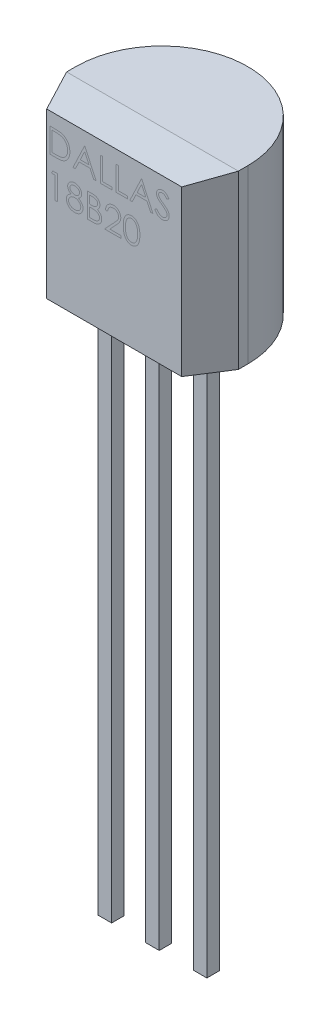
SolidWorks part; units mm, degrees
ref_plane "Front Plane" through (0, 0, 0) normal (0, 0, 1) x (1, 0, 0)
ref_plane "Top Plane" through (0, 0, 0) normal (0, 1, 0) x (1, 0, 0)
ref_plane "Right Plane" through (0, 0, 0) normal (1, 0, 0) x (0, 0, -1)
sketch "Sketch1" plane through (0, 0, 0) normal (0, 1, 0) x (1, 0, 0)
  line L0 (-3.017, 0) -> (3.017, 0) construction
  line L4 (-2.29, 0) -> (-2.29, -0.25)
  line L5 (-2.29, -0.25) -> (2.29, -0.25)
  line L6 (2.29, -0.25) -> (2.29, 0)
  arc A1 (-2.29, 0) -> (2.29, 0) centre (0, 0) cw
  point P4 (0, 0)
  dimension "D1" = 2.29
  dimension "D2" = 0.25
extrude "Boss-Extrude1" add sketch "Sketch1" along normal blind 4.58
sketch "Sketch2" plane through (0, 0, 0.25) normal (0, 0, 1) x (1, 0, 0)
  line L4 (-2.29, 0) -> (2.29, 0)
  line L5 (2.29, 0) -> (2.29, 4.58)
  line L6 (2.29, 4.58) -> (-2.29, 4.58)
  line L7 (-2.29, 4.58) -> (-2.29, 0)
  line L8 (-2.29, 0) -> (2.29, 0)
  line L9 (2.29, 0) -> (2.29, 4.58)
  line L10 (2.29, 4.58) -> (-2.29, 4.58)
  line L11 (-2.29, 4.58) -> (-2.29, 0)
  dimension "D1" = 0
ref_plane "Plane1" through (0, 0, 1.27) normal (0, 0, 1) x (1, 0, 0)
ref_plane "Plane2" through (0, 0, -2.29) normal (0, 0, 1) x (1, 0, 0)
sketch "Sketch3" plane through (0, 0, 1.27) normal (0, 0, 1) x (1, 0, 0)
  line L0 (0, 0) -> (0, 4.58) construction
  line L1 (2.29, 4.58) -> (-2.29, 4.58) construction
  line L3 (-1.8, 0.1) -> (1.8, 0.1)
  line L4 (-1.8, 0.1) -> (-1.8, 4.48)
  line L5 (-1.8, 4.48) -> (1.8, 4.48)
  line L6 (1.8, 0.1) -> (1.8, 4.48)
  line L7 (0, 4.48) -> (0, 0.1) construction
  line L8 (-1.8, 2.29) -> (1.8, 2.29) construction
  point P5 (0, 2.29)
  dimension "D1" = 4.38
  dimension "D2" = 3.6
loft "Loft1" add profiles "Sketch2", "Sketch3"
sketch "Sketch4" plane through (0, 0, 0) normal (0, -1, 0) x (1, 0, 0)
  line L0 (-2.29, 0.25) -> (2.29, 0.25) construction
  line L1 (-0.18, 0.25) -> (0.18, 0.25)
  line L2 (-0.18, 0.25) -> (-0.18, -0.08)
  line L3 (-0.18, -0.08) -> (0.18, -0.08)
  line L4 (0.18, 0.25) -> (0.18, -0.08)
  line L5 (0, 0.25) -> (0, -0.08) construction
  line L6 (-1.45, 0.25) -> (-1.09, 0.25)
  line L7 (-1.45, -0.08) -> (-1.09, -0.08)
  line L8 (-1.45, 0.25) -> (-1.45, -0.08)
  line L9 (-1.09, 0.25) -> (-1.09, -0.08)
  line L10 (-1.27, 0.25) -> (-1.27, -0.08) construction
  line L11 (1.27, 0.25) -> (1.27, -0.08) construction
  line L12 (1.09, 0.25) -> (1.09, -0.08)
  line L13 (1.45, 0.25) -> (1.45, -0.08)
  line L14 (1.45, -0.08) -> (1.09, -0.08)
  line L15 (1.45, 0.25) -> (1.09, 0.25)
  point P6 (0, -0.08)
  dimension "D1" = 0.36
  dimension "D2" = 0.33
  dimension "D3" = 1.27
extrude "Boss-Extrude2" add sketch "Sketch4" along normal blind 14.47
sketch "Sketch5" plane through (0, 0, 1.27) normal (0, 0, 1) x (1, 0, 0)
  line L0 (-1.8, 3.48) -> (1.8, 3.48) construction
  line L1 (-1.8, 4.48) -> (-1.8, 0.1) construction
  line L2 (1.8, 0.1) -> (1.8, 4.48) construction
  line L3 (-1.8, 2.48) -> (1.8, 2.48) construction
  line L4 (1.8, 4.48) -> (-1.8, 4.48) construction
  text T0 "DALLAS" font "Century Gothic" height 0.65
  text T1 "18B20" font "Century Gothic" height 0.65
  point P6 (0, 0)
  dimension "D2" = 1
  dimension "D1" = 1
split line "Split Line1"
sketch "Sketch7" plane through (0, 0, -2.29) normal (0, 0, 1) x (1, 0, 0)
  line L2 (-2.29, 4.58) -> (-2.29, 0) construction
  circle A0 centre (0, 2.29) radius 0.7633
  point P1 (-2.29, 2.29)
  dimension "D3" = 1.5267
  dimension "D1" = 2.29
  dimension "D2" = 2.29
extrude "Cut-Extrude1" cut sketch "Sketch7" along normal blind 0.25
